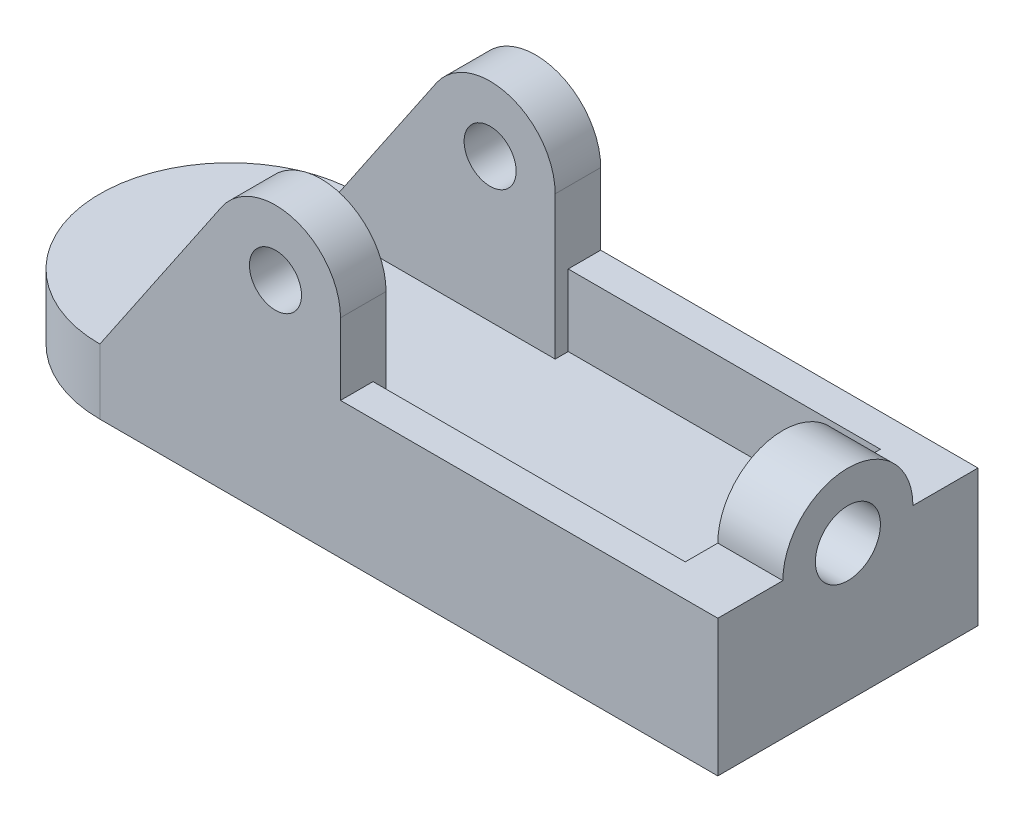
SolidWorks part; units mm, degrees
ref_plane "Front Plane" through (0, 0, 0) normal (0, 0, 1) x (1, 0, 0)
ref_plane "Top Plane" through (0, 0, 0) normal (0, 1, 0) x (1, 0, 0)
ref_plane "Right Plane" through (0, 0, 0) normal (1, 0, 0) x (0, 0, -1)
sketch "Sketch1" plane through (0, 0, 0) normal (0, 1, 0) x (1, 0, 0)
  line L0 (-43.1608, 0) -> (109.9455, 0) construction
  line L1 (0, -20) -> (95, -20)
  line L2 (95, -20) -> (95, 20)
  line L3 (95, 20) -> (0, 20)
  line L4 (0, -5) -> (16.8307, -5)
  line L5 (0, 5) -> (16.8307, 5)
  arc A0 (0, 20) -> (0, -20) centre (0, 0) ccw
  arc A1 (0, 5) -> (0, -5) centre (0, 0) ccw
  arc A2 (16.8307, -5) -> (16.8307, 5) centre (16.8307, 0) ccw
  dimension "D2" = 20
  dimension "D5" = 40
  dimension "D1" = 95
  dimension "D3" = 10
  dimension "D4" = 5
extrude "Boss-Extrude1" add sketch "Sketch1" along normal blind 10
sketch "Sketch2" plane through (0, 0, 20) normal (0, 0, 1) x (1, 0, 0)
  line L0 (0, 10) -> (37, 10)
  line L1 (0, 10) -> (95, 10) construction
  line L2 (37, 10) -> (37, 32)
  line L3 (0, 10) -> (18.7234, 37.6122)
  line L4 (0, 0) -> (95, 0) construction
  arc A0 (37, 32) -> (18.7234, 37.6122) centre (27, 32) ccw
  circle A1 centre (27, 32) radius 4
  dimension "D2" = 22
  dimension "D4" = 8
  dimension "D5" = 10
  dimension "D1" = 37
  dimension "D3" = 32
extrude "Boss-Extrude2" add sketch "Sketch2" against normal blind 7
mirror "Mirror1" about plane through (0, 0, 0) normal (0, 0, 1) of "Boss-Extrude2"
sketch "Sketch4" plane through (0, 10, 0) normal (0, 1, 0) x (1, 0, 0)
  line L0 (37, -20) -> (95, -20)
  line L1 (95, -20) -> (95, -10)
  line L2 (95, -20) -> (95, 20) construction
  line L3 (95, -10) -> (85, -10)
  line L4 (85, -10) -> (85, -15)
  line L5 (85, -15) -> (37, -15)
  line L8 (37, -15) -> (37, -20)
  dimension "D1" = 5
  dimension "D2" = 10
  dimension "D3" = 10
extrude "Boss-Extrude3" add sketch "Sketch4" along normal blind 11
mirror "Mirror2" about plane through (0, 0, 0) normal (0, 0, 1) of "Boss-Extrude3"
sketch "Sketch5" plane through (95, 0, 0) normal (1, 0, 0) x (0, 0, -1)
  line L0 (0, 7.0015) -> (0, 43.1328) construction
  line L2 (-10, 10) -> (10, 10)
  line L3 (10, 10) -> (10, 21)
  line L4 (-10, 10) -> (-10, 21)
  line L5 (-10, 10) -> (10, 10) construction
  circle A0 centre (0, 21) radius 5
  arc A1 (-10, 21) -> (10, 21) centre (0, 21) cw
  dimension "D1" = 10
  dimension "D3" = 10
extrude "Boss-Extrude4" add sketch "Sketch5" against normal blind 10
